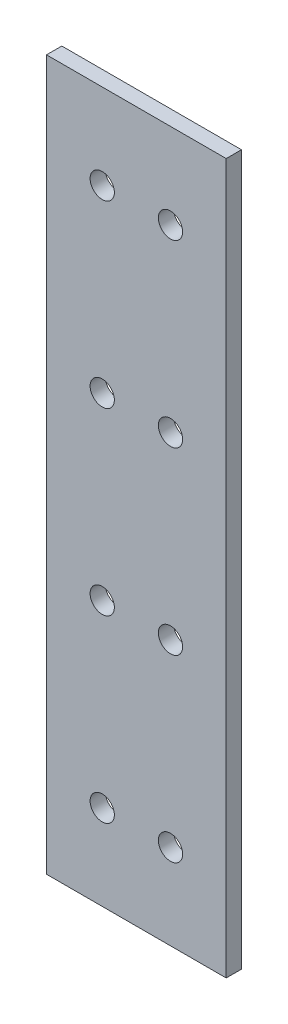
SolidWorks part; units mm, degrees
material "ABS"
ref_plane "Front Plane" through (0, 0, 0) normal (0, 0, 1) x (1, 0, 0)
ref_plane "Top Plane" through (0, 0, 0) normal (0, 1, 0) x (1, 0, 0)
ref_plane "Right Plane" through (0, 0, 0) normal (1, 0, 0) x (0, 0, -1)
sketch "Sketch1" plane through (0, 0, 0) normal (0, 0, 1) x (1, 0, 0)
  line L1 (-10, -39.5) -> (10, -39.5)
  line L2 (-10, -39.5) -> (-10, 39.5)
  line L3 (-10, 39.5) -> (10, 39.5)
  line L4 (10, -39.5) -> (10, 39.5)
  line L5 (-10, -39.5) -> (10, 39.5) construction
  line L6 (-10, 39.5) -> (10, -39.5) construction
  point P0 (0, 0)
  dimension "D1" = 20
  dimension "D2" = 79
extrude "Boss-Extrude1" add sketch "Sketch1" along normal blind 1.7
sketch "Sketch3" plane through (0, 0, 1.7) normal (0, 0, 1) x (1, 0, 0)
  line L0 (0, 0) -> (0, 39.5) construction
  line L1 (10, 39.5) -> (-10, 39.5) construction
  line L2 (0, 0) -> (-3.8, -10) construction
  line L3 (-3.8, 10) -> (0, 0) construction
  circle A0 centre (-3.8, 30) radius 1.35
  circle A1 centre (-3.8, 10) radius 1.35
  circle A2 centre (-3.8, -10) radius 1.35
  circle A3 centre (-3.8, -30) radius 1.35
  circle A4 centre (3.8, -30) radius 1.35
  circle A5 centre (3.8, -10) radius 1.35
  circle A6 centre (3.8, 10) radius 1.35
  circle A7 centre (3.8, 30) radius 1.35
  dimension "D1" = 2.7
  dimension "D2" = 3.8
  dimension "D4" = 20
  dimension "D3" = 4
extrude "Cut-Extrude1" cut sketch "Sketch3" against normal through all
equation "\"smallPulleyTeeth\"= 30"
equation "\"largePulleyTeeth\"= 30"
equation "\"eighthThick\"= 3.0mm"
equation "\"sixteenthThick\"= 1.7mm"
equation "\"quarterThick\"=6.0mm"
equation "\"OD\"= 145mm"
equation "\"puckAngle\"= 60.5deg"
equation "\"puckDiam\"= 76.5mm"
equation "\"puckDist\"= 85mm"
equation "\"scoopFillet\"= 5mm"
equation "\"axlePress\"= 5.9mm"
equation "\"press\"= 0.2mm"
equation "\"wheelClear\"= 0.3mm"
equation "\"10-32clear\"= 4.8mm"
equation "\"10-32tap\"= 4.45mm"
equation "\"6-32clear\"= 3.3mm"
equation "\"8-32clear\"= 4.0mm"
equation "\"4-40clear\"= 3.0mm"
equation "\"wheelHeight\"= 22mm"
equation "\"wheelWell\"= 65mm"
equation "\"ledSmall\"= 3.1mm"
equation "\"ledLarge\"= 4.2mm"
equation "\"ledLength\"= 4.2mm"
equation "\"4-40close\"= 2.7mm"
equation "\"4-40nutThick\"= 2.2mm"
equation "\"4-40nutWidth\"= 6.2mm"
equation "\"4-40insertHeight\"= 3.5mm"
equation "\"4-40insert\"= 4mm"
equation "\"D1@Boss-Extrude1\"=\"sixteenthThick\""
equation "\"D1@Sketch3\"=\"4-40close\""
